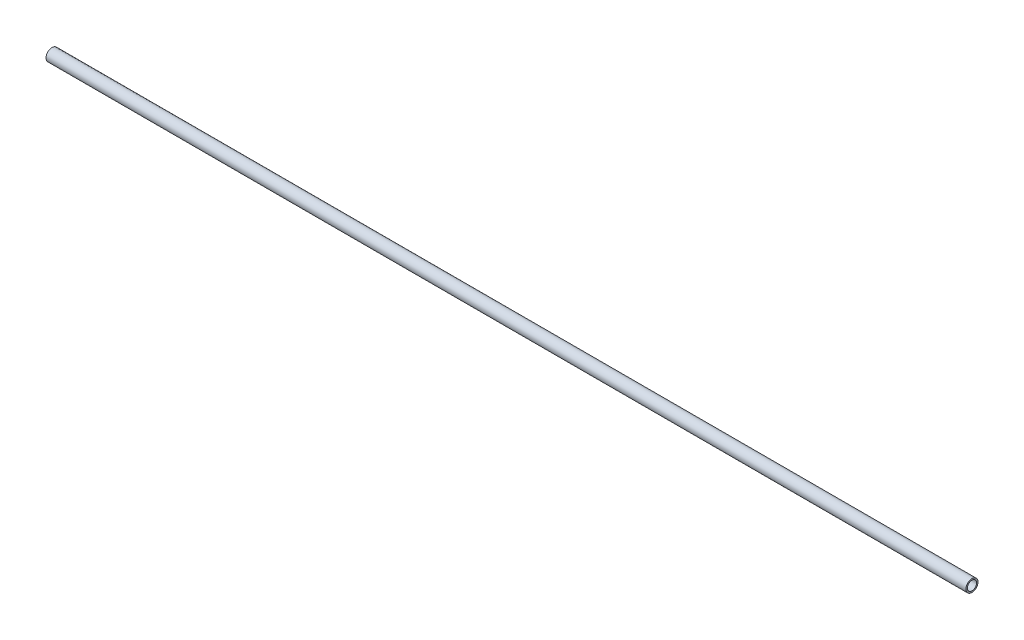
SolidWorks part; units mm, degrees
material "AISI 1010 Steel, hot rolled bar"
ref_plane "Front Plane" through (0, 0, 0) normal (0, 0, 1) x (1, 0, 0)
ref_plane "Top Plane" through (0, 0, 0) normal (0, 1, 0) x (1, 0, 0)
ref_plane "Right Plane" through (0, 0, 0) normal (1, 0, 0) x (0, 0, -1)
sketch "Sketch1" plane through (0, 0, 0) normal (1, 0, 0) x (0, 0, -1)
  circle A0 centre (0, 0) radius 12.7
  circle A1 centre (0, 0) radius 9.652
  dimension "D1" = 25.4
  dimension "D2" = 19.304
extrude "Boss-Extrude1" add sketch "Sketch1" along normal blind 1930.4
